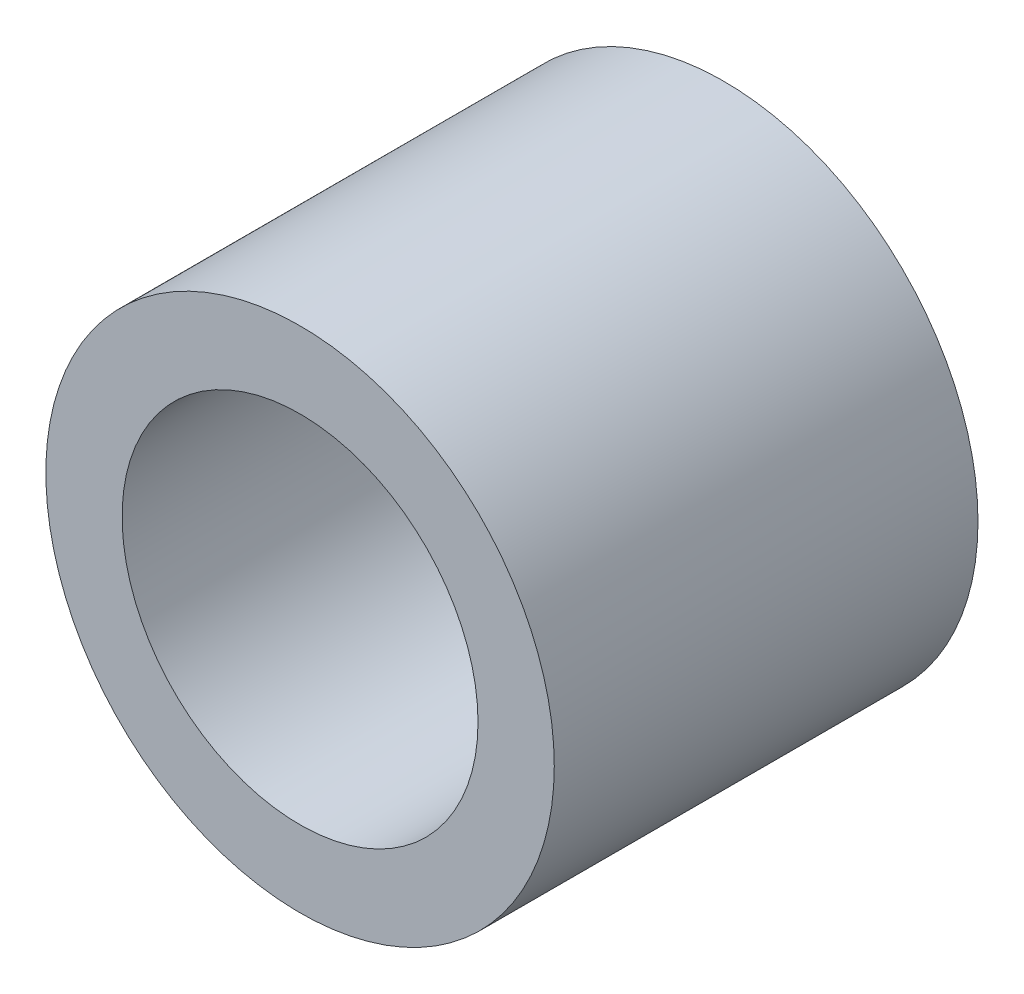
SolidWorks part; units mm, degrees
material "AISI 4340 Steel, normalized"
ref_plane "Front Plane" through (0, 0, 0) normal (0, 0, 1) x (1, 0, 0)
ref_plane "Top Plane" through (0, 0, 0) normal (0, 1, 0) x (1, 0, 0)
ref_plane "Right Plane" through (0, 0, 0) normal (1, 0, 0) x (0, 0, -1)
sketch "Sketch1" plane through (0, 0, 0) normal (0, 0, 1) x (1, 0, 0)
  circle A0 centre (0, 0) radius 1.5
  circle A1 centre (0, 0) radius 1.05
extrude "Spacer" add sketch "Sketch1" along normal blind 2.5
